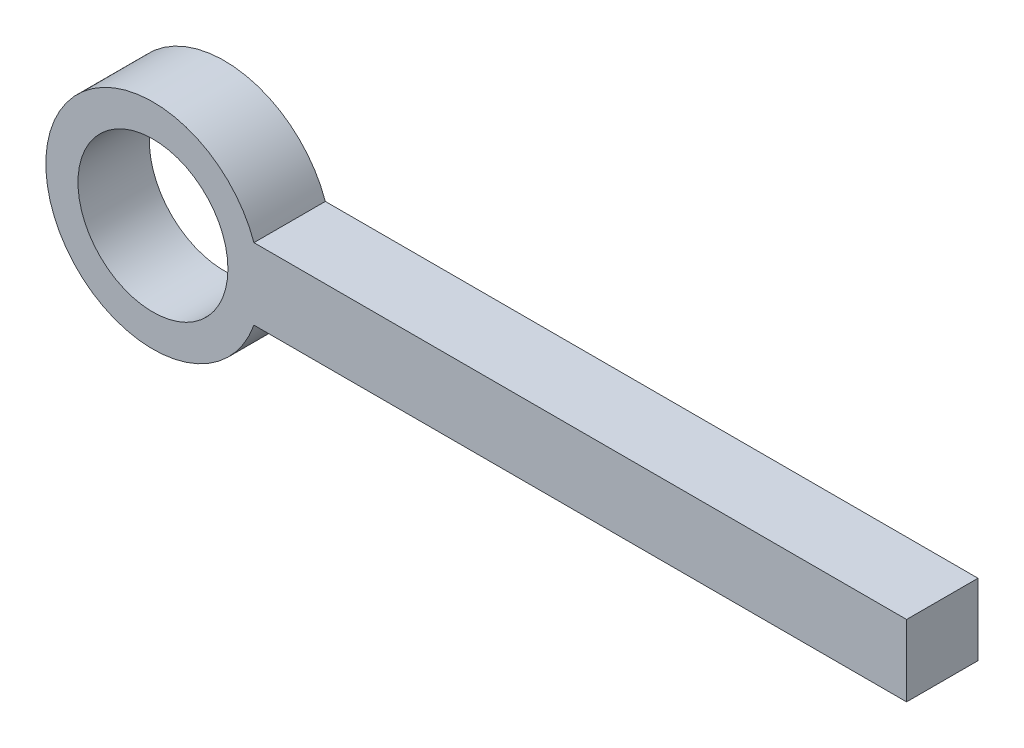
SolidWorks part; units mm, degrees
ref_plane "Ön Düzlem" through (0, 0, 0) normal (0, 0, 1) x (1, 0, 0)
ref_plane "Üst Düzlem" through (0, 0, 0) normal (0, 1, 0) x (1, 0, 0)
ref_plane "Sağ Düzlem" through (0, 0, 0) normal (1, 0, 0) x (0, 0, -1)
sketch "Çizim1" plane through (0, 0, 0) normal (0, 0, 1) x (1, 0, 0)
  line L0 (-53.0219, 0) -> (80.2951, 0) construction
  line L1 (80.2951, 5) -> (-11.0983, 5)
  line L2 (-11.0983, -5) -> (80.2951, -5)
  line L3 (80.2951, -5) -> (80.2951, 5)
  arc A1 (-11.0983, 5) -> (-11.0983, -5) centre (-25.2404, 0) ccw
  circle A2 centre (-25.2404, 0) radius 10.5
  dimension "D1" = 21
  dimension "D4" = 30
  dimension "D2" = 5
  dimension "D3" = 5
extrude "Yükseklik-Ekstrüzyon1" add sketch "Çizim1" along normal blind 10
